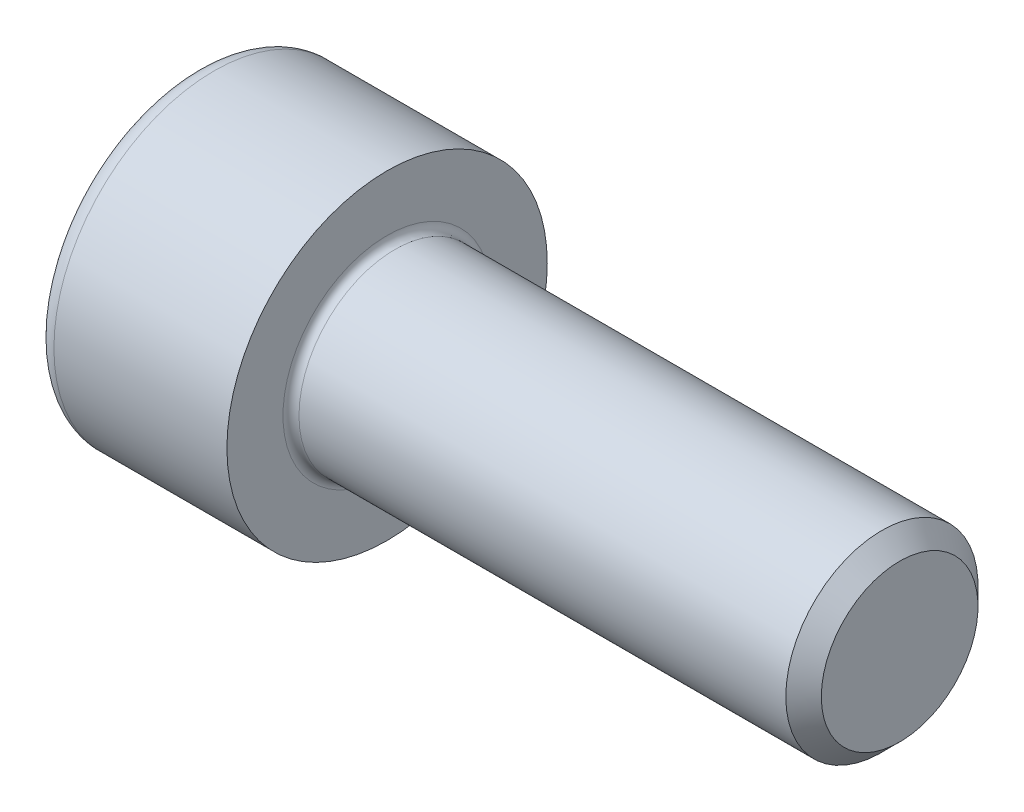
SolidWorks part; units mm, degrees
ref_plane "Front Plane" through (0, 0, 0) normal (0, 0, 1) x (1, 0, 0)
ref_plane "Top Plane" through (0, 0, 0) normal (0, 1, 0) x (1, 0, 0)
ref_plane "Right Plane" through (0, 0, 0) normal (1, 0, 0) x (0, 0, -1)
sketch "BaseHeadSke" plane through (0, 0, 0) normal (1, 0, 0) x (0, 0, -1)
  circle A1 centre (0, 0) radius 5
  dimension "Head_diameter" = 10
extrude "BaseHead" add sketch "BaseHeadSke" along normal blind 6
sketch "BodySke" plane through (0, 0, 0) normal (0, 0, 1) x (1, 0, 0)
  line L0 (0, 0) -> (22, 0)
  line L1 (22, 0) -> (22, 2.4455)
  line L2 (22, 2.4455) -> (21.4455, 3)
  line L3 (21.4455, 3) -> (0, 3)
  line L4 (0, 3) -> (0, 0)
  line L6 (0, 0) -> (159.3976, 0) construction
  line L7 (6, -84.3176) -> (6, 77.7215) construction
  line L8 (21, -21.5941) -> (21, 39.2994) construction
  line L10 (6, -5) -> (6, 5) construction
  dimension "Ang" = 45
  dimension "Diameter" = 6
  dimension "Minor_dia" = 4.891
  dimension "Thread_length" = 16
  dimension "Advance" = 1
  dimension "Length" = 16
revolve "BaseBody" add sketch "BodySke" angle 360 about L6
cosmetic thread "ThreadCosmetic" [suppressed] parameters "Thread_length"=16, "Thread_minor"=4.891
sketch "CutSocketSke" plane through (0, 0, 0) normal (1, 0, 0) x (0, 0, -1)
  line L1 (0, 2.8868) -> (-2.5, 1.4434)
  line L2 (-2.5, 1.4434) -> (-2.5, -1.4434)
  line L3 (-2.5, -1.4434) -> (0, -2.8868)
  line L4 (0, -2.8868) -> (2.5, -1.4434)
  line L5 (2.5, -1.4434) -> (2.5, 1.4434)
  line L6 (2.5, 1.4434) -> (0, 2.8868)
  circle A0 centre (0, 0) radius 2.5 construction
  dimension "Socket_width" = 5
extrude "CutSocket" cut sketch "CutSocketSke" along normal blind 3
sketch "CutHoleSke" plane through (0, 0, 0) normal (0, 0, 1) x (1, 0, 0)
  line L0 (0, 0) -> (149.4323, 0) construction
  line L1 (0, 2.5) -> (3.7, 2.5)
  line L2 (3.7, 2.5) -> (5.1434, 0)
  line L3 (5.1434, 0) -> (0, 0)
  line L4 (0, 0) -> (0, 2.5)
  line L6 (6, -5) -> (6, 5) construction
  dimension "D1" = 60
  dimension "Hole_depth" = 2.3
  dimension "D2" = 5
revolve "CutHole" cut sketch "CutHoleSke" angle 360 about L0
fillet "Fillet1" radius 0.25 1 edges at (6, 0, -3)
fillet "Fillet2" radius 0.6 1 edges at (0, 0, -5)
sketch "ThdSchSke" plane through (0, 0, 0) normal (0, 0, 1) x (1, 0, 0)
  line L0 (20.6799, 3.6403) -> (20.6799, 3)
  line L1 (20.6799, 3) -> (21, 2.4455)
  line L2 (21, 2.4455) -> (21.3201, 3)
  line L3 (21.3201, 3) -> (21.3201, 3.6403)
  line L4 (21.3201, 3.6403) -> (20.6799, 3.6403)
  line L6 (0, 0) -> (141.9934, 0) construction
  line L7 (22, -2.4455) -> (22, 2.4455) construction
  dimension "Advance" = 1
  dimension "D2" = 4.891
  dimension "D3" = 6
revolve "ThreadSchematic" [suppressed] cut sketch "ThdSchSke" angle 360 about L6
pattern_linear "ThdSchPat" [suppressed] count 15 spacing 1 along (1, 0, 0)
equation "\"Thread_minor@ThreadCosmetic\" = \"Minor_dia@BodySke\""
equation "\"Thread_length@ThreadCosmetic\" = \"Thread_length@BodySke\""
equation "\"D2@CutHoleSke\" = \"Socket_width@CutSocketSke\""
equation "\"D2@ThdSchSke\" = \"Minor_dia@BodySke\""
equation "\"D3@ThdSchSke\" = \"Diameter@BodySke\""
equation "\"Advance@ThdSchSke\" = \"Advance@BodySke\""
equation "\"D3@ThdSchPat\" = \"Advance@BodySke\""
equation "\"D1@ThdSchPat\" =  int( \"Thread_length@BodySke\"/\"Advance@BodySke\" )-1"
